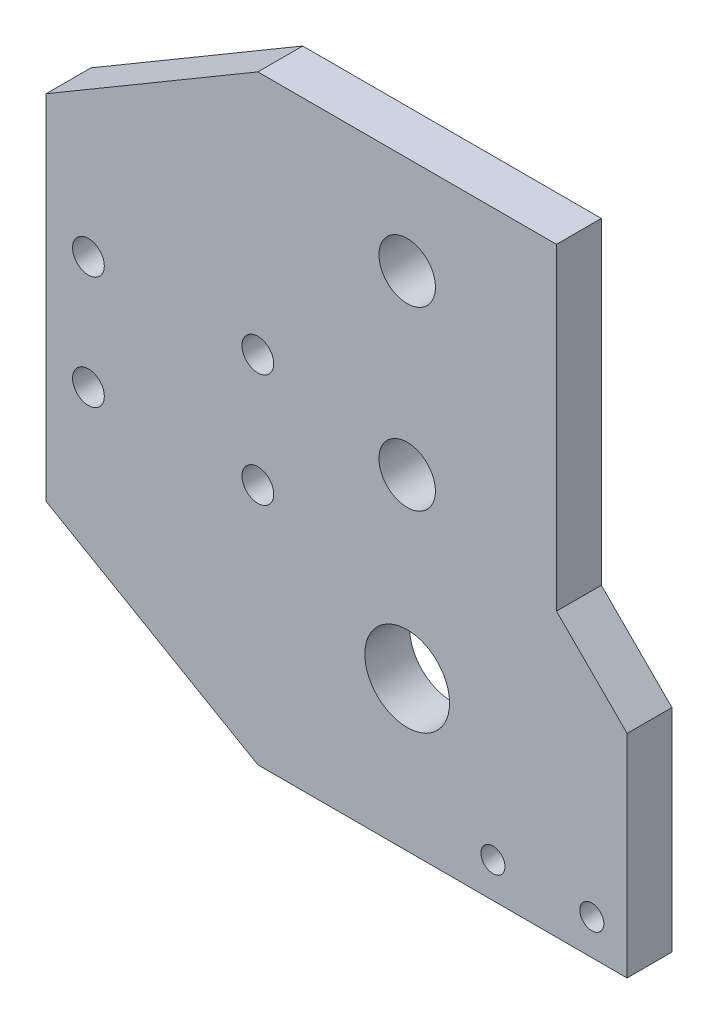
SolidWorks part; units mm, degrees
material "6061 Alloy"
ref_plane "Front Plane" through (0, 0, 0) normal (0, 0, 1) x (1, 0, 0)
ref_plane "Top Plane" through (0, 0, 0) normal (0, 1, 0) x (1, 0, 0)
ref_plane "Right Plane" through (0, 0, 0) normal (1, 0, 0) x (0, 0, -1)
sketch "Sketch2" plane through (0, 0, 0) normal (0, 0, 1) x (1, 0, 0)
  line L0 (0, 0) -> (0, -21.15) construction
  line L1 (-21.15, -21.15) -> (21.15, -21.15)
  line L2 (-21.15, -21.15) -> (-21.15, 63.85)
  line L3 (-21.15, 63.85) -> (21.15, 63.85)
  line L4 (21.15, -21.15) -> (21.15, 63.85)
  circle A0 centre (0, 0) radius 6
  circle A1 centre (0, 25) radius 4
  circle A2 centre (0, 50) radius 4
  dimension "D1" = 12
  dimension "D5" = 25
  dimension "D7" = 8
  dimension "D2" = 21.15
  dimension "D3" = 42.3
  dimension "D4" = 85
  dimension "D6" = 25
extrude "Boss-Extrude1" add sketch "Sketch2" along normal blind 6.35
sketch "Sketch8" plane through (0, 0, 6.35) normal (0, 0, 1) x (1, 0, 0)
  line L0 (-21.15, -21.15) -> (-51.15, -3.8295)
  line L1 (-51.15, -3.8295) -> (-51.15, 46.1705)
  line L2 (-51.15, 46.1705) -> (-21.15, 63.85)
  line L3 (-21.15, 63.85) -> (-21.15, -21.15) construction
  line L4 (-21.15, 63.85) -> (-21.15, -21.15)
  dimension "D2" = 60
  dimension "D3" = 30
  dimension "D4" = 50
extrude "Boss-Extrude2" add sketch "Sketch8" against normal up to surface (6.35 mm away) up to face at (4, 25, 0)
sketch "Sketch9" plane through (0, 0, 6.35) normal (0, 0, 1) x (1, 0, 0)
  line L0 (-51.15, 21.1705) -> (-33.15, 21.1705) construction
  line L1 (-51.15, 46.1705) -> (-51.15, -3.8295) construction
  line L3 (-45.15, 13.1705) -> (-21.15, 13.1705) construction
  line L4 (-45.15, 13.1705) -> (-45.15, 29.1705) construction
  line L5 (-45.15, 29.1705) -> (-21.15, 29.1705) construction
  line L6 (-21.15, 13.1705) -> (-21.15, 29.1705) construction
  line L7 (-45.15, 13.1705) -> (-21.15, 29.1705) construction
  line L8 (-45.15, 29.1705) -> (-21.15, 13.1705) construction
  point P4 (-21.15, 29.1705)
  point P5 (-45.15, 13.1705)
  point P6 (-45.15, 29.1705)
  point P7 (-21.15, 13.1705)
  dimension "D1" = 18
  dimension "D2" = 16
  dimension "D3" = 24
hole_wizard "M4 Clearance Hole1" positions "Sketch9" profile "Sketch10" hole size "M4" standard "ANSI Metric" end condition through all
sketch "Sketch10" plane through (-21.15, 13.1705, 6.35) normal (1, 0, 0) x (0, -1, 0)
  line L0 (0, 0) -> (0, 6.35)
  line L1 (0, 6.35) -> (2.25, 6.35)
  line L2 (2.25, 6.35) -> (2.25, 0)
  line L5 (2.25, 0) -> (0, 0)
  line L11 (0, -6.35) -> (0, 107.95) construction
  dimension "Thru Hole Dia." = 4.5
  dimension "Thru Hole Depth" = 6.35
sketch "Sketch11" plane through (0, 0, 6.35) normal (0, 0, 1) x (1, 0, 0)
  line L0 (21.15, -21.15) -> (31.15, -21.15)
  line L1 (31.15, -21.15) -> (31.15, 8.85)
  line L2 (31.15, 8.85) -> (21.15, 18.85)
  line L3 (21.15, -21.15) -> (21.15, 63.85) construction
  line L4 (21.15, 18.85) -> (21.15, -21.15)
  dimension "D1" = 10
  dimension "D2" = 30
  dimension "D3" = 45
extrude "Boss-Extrude3" add sketch "Sketch11" against normal up to surface (6.35 mm away) up to face at (-18.9, 29.1705, 0)
sketch "Sketch14" plane through (0, 0, 6.35) normal (0, 0, 1) x (1, 0, 0)
  line L0 (12.15, -16.15) -> (26.15, -16.15) construction
  line L1 (31.15, -21.15) -> (31.15, 8.85) construction
  line L2 (-21.15, -21.15) -> (31.15, -21.15) construction
  point P0 (12.15, -16.15)
  point P1 (26.15, -16.15)
  dimension "D1" = 14
  dimension "D2" = 5
  dimension "D3" = 5
hole_wizard "M3 Clearance Hole2" positions "Sketch14" profile "Sketch15" hole size "M3" standard "ANSI Metric" end condition through all
sketch "Sketch15" plane through (12.15, -16.15, 6.35) normal (1, 0, 0) x (0, -1, 0)
  line L0 (0, 0) -> (0, 6.35)
  line L1 (0, 6.35) -> (1.7, 6.35)
  line L2 (1.7, 6.35) -> (1.7, 0)
  line L5 (1.7, 0) -> (0, 0)
  line L11 (0, -6.35) -> (0, 107.95) construction
  dimension "Thru Hole Dia." = 3.4
  dimension "Thru Hole Depth" = 6.35
sketch "Sketch3" plane through (31.15, 0, 0) normal (-1, 0, 0) x (0, 0, 1)
  line L0 (6.35, -6) -> (6.35, 6) construction
  line L1 (6.35, 21) -> (6.35, 29) construction
  line L2 (6.35, 46) -> (6.35, 54) construction
  line L3 (6.35, -6) -> (6.35, 6) construction
  line L4 (6.35, 21) -> (6.35, 29) construction
  line L5 (6.35, 46) -> (6.35, 54) construction
  line L6 (3.175, 63.85) -> (3.175, -21.15) construction
  line L9 (6.35, 0) -> (3.175, 0) construction
  line L10 (6.35, 25) -> (3.175, 25) construction
  line L11 (6.35, 50) -> (3.175, 50) construction
  line L12 (6.35, -21.15) -> (0, -21.15) construction
  line L13 (6.35, 63.85) -> (0, 63.85) construction
  point P13 (3.175, 0)
  point P16 (3.175, 25)
  point P18 (3.175, 50)
  point P26 (3.175, 63.85)
